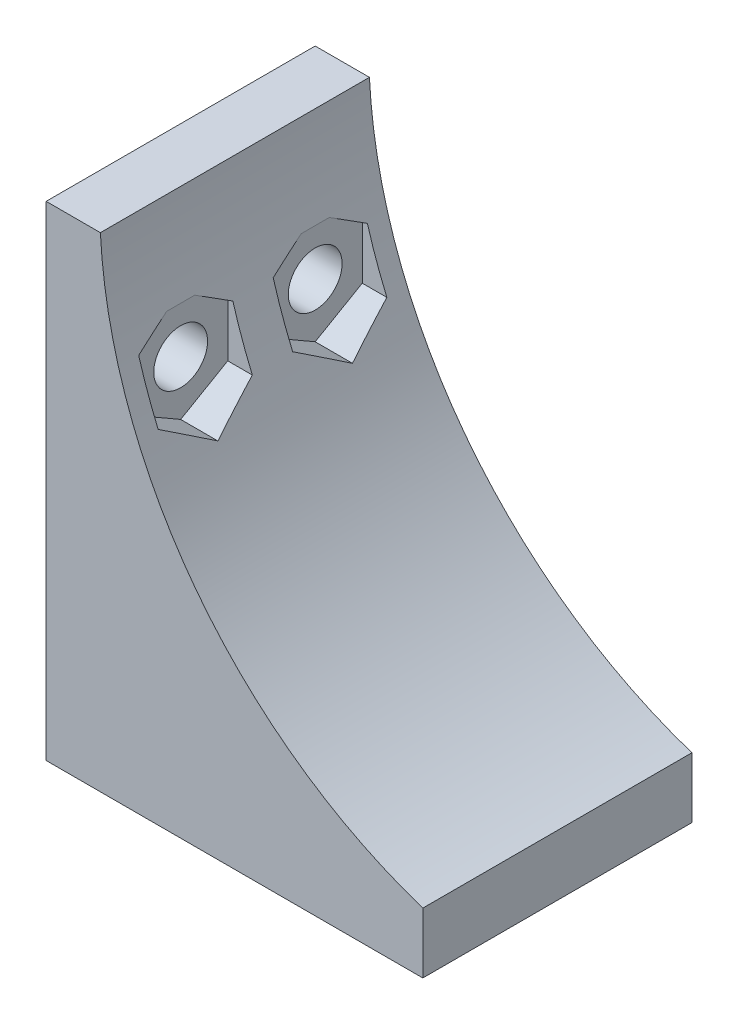
SolidWorks part; units mm, degrees
ref_plane "前视基准面" through (0, 0, 0) normal (0, 0, 1) x (1, 0, 0)
ref_plane "上视基准面" through (0, 0, 0) normal (0, 1, 0) x (1, 0, 0)
ref_plane "右视基准面" through (0, 0, 0) normal (1, 0, 0) x (0, 0, -1)
sketch "草图1" plane through (0, 0, 0) normal (0, 0, 1) x (1, 0, 0)
  line L0 (0, 36) -> (0, 0)
  line L1 (0, 0) -> (28, 0)
  line L2 (0, 0) -> (39.1084, 37.8203) construction
  line L3 (28, 0) -> (28, 36) construction
  line L4 (28, 36) -> (0, 36) construction
  line L5 (28, 0) -> (28, 4.5)
  line L6 (0, 36) -> (4.0324, 36)
  arc A0 (4.0324, 36) -> (28, 4.5) centre (39.1084, 37.8203) ccw
  point P4 (34.9587, 36.7403)
  point P7 (8.4301, 38)
  point P9 (50.0704, 43.8552)
  point P11 (4.6007, 38)
  point P12 (39.155, 38)
  dimension "D1" = 28
  dimension "D2" = 36
  dimension "D5" = 4.5
extrude "凸台-拉伸1" add sketch "草图1" along normal mid plane 20
sketch "草图2" plane through (0, 0, 0) normal (1, 0, 0) x (0, 0, -1)
  line L0 (-10, 26) -> (10, 26) construction
  line L1 (-10, 36) -> (-10, 4.5) construction
  line L2 (10, 4.5) -> (10, 36) construction
  line L3 (-10, 36) -> (10, 36) construction
  line L4 (0, 36) -> (0, 0) construction
  circle A0 centre (-5, 26) radius 2
  circle A1 centre (5, 26) radius 2
  dimension "D2" = 4
  dimension "D3" = 10
  dimension "D1" = 10
extrude "切除-拉伸2" cut sketch "草图2" against normal mid plane 20
ref_plane "基准面1" through (5, 0, 0) normal (1, 0, 0) x (0, 0, -1)
sketch "草图3" plane through (5, 0, 0) normal (1, 0, 0) x (0, 0, -1)
  line L1 (-5, 30.0415) -> (-8.5, 28.0207)
  line L2 (-8.5, 28.0207) -> (-8.5, 23.9793)
  line L3 (-8.5, 23.9793) -> (-5, 21.9585)
  line L4 (-5, 21.9585) -> (-1.5, 23.9793)
  line L5 (-1.5, 23.9793) -> (-1.5, 28.0207)
  line L6 (-1.5, 28.0207) -> (-5, 30.0415)
  line L7 (5, 30.0415) -> (1.5, 28.0207)
  line L8 (1.5, 28.0207) -> (1.5, 23.9793)
  line L9 (1.5, 23.9793) -> (5, 21.9585)
  line L10 (5, 21.9585) -> (8.5, 23.9793)
  line L11 (8.5, 23.9793) -> (8.5, 28.0207)
  line L12 (8.5, 28.0207) -> (5, 30.0415)
  circle A0 centre (-5, 26) radius 3.5 construction
  circle A1 centre (5, 26) radius 3.5 construction
  dimension "D1" = 7
extrude "切除-拉伸3" cut sketch "草图3" along normal blind 20
